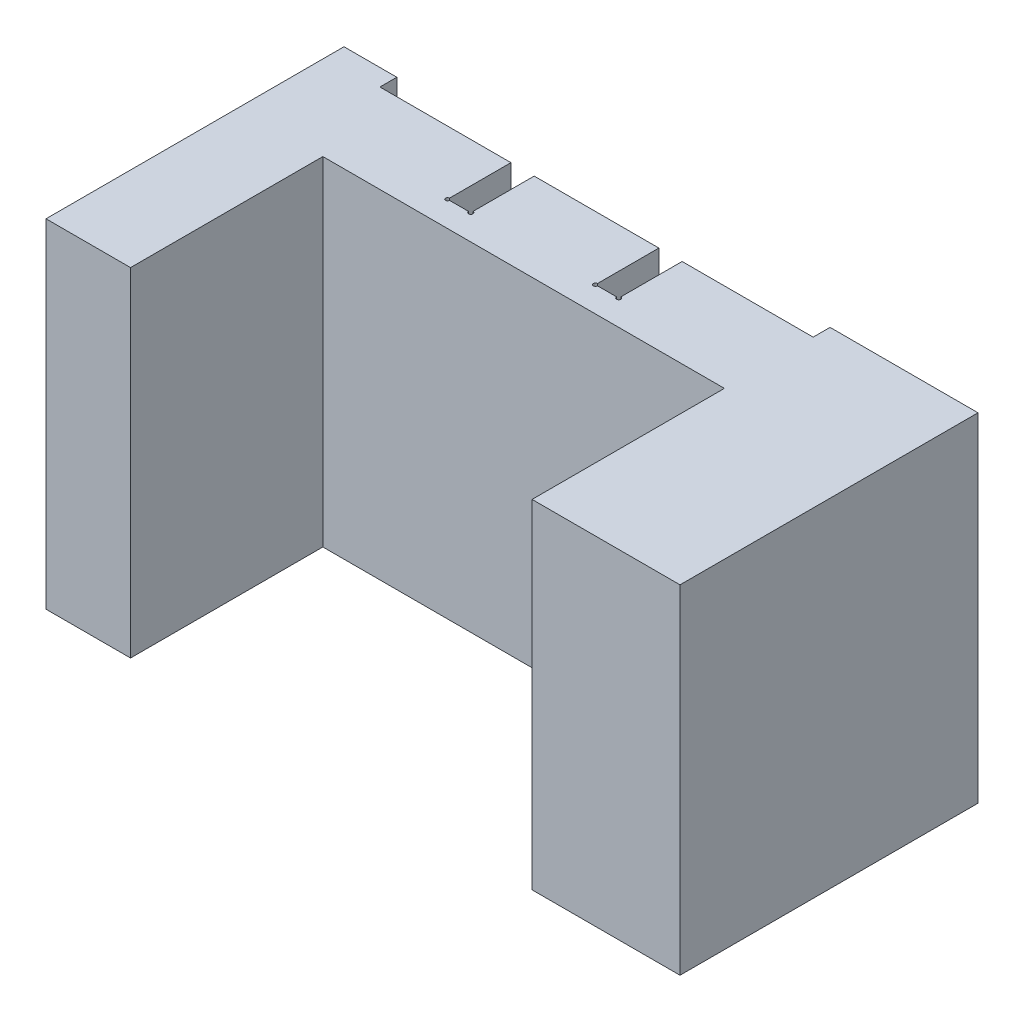
SolidWorks part; units mm, degrees
ref_plane "前视基准面" through (0, 0, 0) normal (0, 0, 1) x (1, 0, 0)
ref_plane "上视基准面" through (0, 0, 0) normal (0, 1, 0) x (1, 0, 0)
ref_plane "右视基准面" through (0, 0, 0) normal (1, 0, 0) x (0, 0, -1)
sketch "草图1" plane through (0, 0, 0) normal (0, 0, 1) x (1, 0, 0)
  line L1 (-7.5503, 16.7364) -> (22.4497, 16.7364)
  line L2 (-7.5503, 16.7364) -> (-7.5503, -11.2636)
  line L3 (-7.5503, -11.2636) -> (22.4497, -11.2636)
  line L4 (22.4497, 16.7364) -> (22.4497, -11.2636)
  dimension "D1" = 30
  dimension "D2" = 28
extrude "凸台-拉伸1" add sketch "草图1" along normal blind 10
sketch "草图2" plane through (0, 0, 0) normal (0, 0, -1) x (-1, 0, 0)
  line L0 (-22.4497, 16.7364) -> (7.5503, 16.7364) construction
  line L1 (7.5503, 16.7364) -> (7.5503, -11.2636) construction
  line L3 (5.0503, 16.7364) -> (-15.4497, 16.7364)
  line L4 (5.0503, 16.7364) -> (5.0503, 3.7364)
  line L5 (2.0503, 0.7364) -> (-12.4497, 0.7364)
  line L6 (-15.4497, 16.7364) -> (-15.4497, 3.7364)
  arc A0 (2.0503, 0.7364) -> (5.0503, 3.7364) centre (2.0503, 3.7364) ccw
  arc A1 (-12.4497, 0.7364) -> (-15.4497, 3.7364) centre (-12.4497, 3.7364) cw
  point P0 (5.0503, 16.7364)
  point P11 (5.0503, 0.7364)
  dimension "D4" = 3
  dimension "D1" = 2.5
  dimension "D2" = 20.5
  dimension "D3" = 16
extrude "切除-拉伸2" cut sketch "草图2" against normal blind 0.8
sketch "草图3" plane through (0, 0, 0.8) normal (0, 0, -1) x (-1, 0, 0)
  line L0 (5.0503, 16.7364) -> (-15.4497, 16.7364) construction
  line L2 (-15.1997, 16.7364) -> (4.8003, 16.7364)
  line L3 (-15.1997, 16.7364) -> (-15.1997, 3.7364)
  line L4 (-12.1997, 0.7364) -> (1.8003, 0.7364)
  line L5 (4.8003, 16.7364) -> (4.8003, 3.7364)
  arc A0 (1.8003, 0.7364) -> (4.8003, 3.7364) centre (1.8003, 3.7364) ccw
  arc A1 (-12.1997, 0.7364) -> (-15.1997, 3.7364) centre (-12.1997, 3.7364) cw
  point P0 (-5.1997, 16.7364)
  point P9 (4.8003, 0.7364)
  point P12 (1.8003, 13.7364)
  point P14 (-12.1997, 13.7364)
  dimension "D4" = 3
  dimension "D1" = 20
  dimension "D2" = 10
  dimension "D3" = 16
  dimension "D5" = 3
  dimension "D6" = 3
  dimension "D7" = 3
  dimension "D8" = 3
hole_wizard "M1.4x0.3 螺纹孔2" positions "草图9" profile "草图7" tap size "M1.4x0.3" standard "ANSI Metric"
sketch "草图9" plane through (0, 0, 0.8) normal (0, 0, -1) x (-1, 0, 0)
  line L0 (-15.1997, 16.7364) -> (4.8003, 16.7364) construction
  point P0 (-12.1997, 8.7364)
  point P3 (1.8003, 8.7364)
  dimension "D1" = 8
  dimension "D2" = 8
sketch "草图7" plane through (12.1997, 8.7364, 0.8) normal (1, 0, 0) x (0, 1, 0)
  line L0 (0, 0) -> (0, 4.0305)
  line L1 (0, 4.0305) -> (0.55, 3.7)
  line L2 (0.55, 3.7) -> (0.55, 0)
  line L5 (0.55, 0) -> (0, 0)
  line L10 (0, 4.0305) -> (-0.55, 3.7) construction
  line L11 (0, -6.35) -> (0, 107.95) construction
  dimension "螺纹孔钻头直径" = 1.1
  dimension "螺纹孔钻头深度" = 3.7
  dimension "导头角度" = 118
cosmetic thread "孔螺蚊线7" parameters "D1"=3.5, "D2"=1.4
cosmetic thread "孔螺蚊线8" parameters "D1"=3.5, "D2"=1.4
sketch "草图27" plane through (0, 0, 0.8) normal (0, 0, -1) x (-1, 0, 0)
  line L2 (-15.4497, 8.7364) -> (5.0503, 8.7364)
  line L3 (5.0503, 16.7364) -> (-15.4497, 16.7364) construction
  point P0 (-15.4497, 12.2364)
  point P1 (5.0503, 12.2364)
  dimension "D1" = 8
sketch "草图10" plane through (0, 16.7364, 0) normal (0, 1, 0) x (1, 0, 0)
  line L0 (22.4497, -0.8) -> (-7.5503, -0.8)
  line L1 (22.4497, -10) -> (22.4497, 0) construction
  line L2 (-7.5503, -10) -> (-7.5503, 0) construction
  line L3 (22.4497, 0) -> (15.4497, 0) construction
  line L5 (9.2497, -0.8) -> (8.1497, -0.8)
  line L6 (9.2497, -0.8) -> (9.2497, -3.7)
  line L7 (9.1495, -3.8) -> (8.2497, -3.8)
  line L8 (8.1497, -0.8) -> (8.1497, -3.7)
  line L9 (1.1497, -0.8) -> (2.2497, -0.8)
  line L10 (1.1497, -0.8) -> (1.1497, -3.7043)
  line L11 (1.2454, -3.8) -> (2.1461, -3.8)
  line L12 (2.2497, -0.8) -> (2.2497, -3.6964)
  arc A0 (9.1495, -3.8) -> (9.2497, -3.7) centre (9.2495, -3.8) ccw
  arc A1 (8.1497, -3.7) -> (8.2497, -3.8) centre (8.1497, -3.8) ccw
  arc A2 (2.1461, -3.8) -> (2.2497, -3.6964) centre (2.2497, -3.8) ccw
  arc A3 (1.1497, -3.7043) -> (1.2454, -3.8) centre (1.1497, -3.8) ccw
  point P8 (5.1997, -0.8)
  point P9 (9.2497, -0.8)
  point P10 (1.1497, -0.8)
  dimension "D9" = 0.1
  dimension "D10" = 0.1
  dimension "D1" = 0.8
  dimension "D2" = 4.05
  dimension "D3" = 4.05
  dimension "D4" = 3
  dimension "D5" = 1.1
  dimension "D6" = 1.1
  dimension "D7" = 3
  dimension "D8" = 12.75
extrude "切除-拉伸3" cut sketch "草图10" against normal blind 4 contours L8 A1 L7 A0 L6 L5 | L10 A3 L11 A2 L12 L9
sketch "草图11" plane through (0, 0, 0) normal (0, 0, -1) x (-1, 0, 0)
  line L0 (-12.1997, 0.7364) -> (1.8003, 0.7364) construction
  line L1 (-7.5497, -2.0636) -> (-2.8497, -2.0636)
  line L2 (-7.7997, 0.7364) -> (-2.5997, 0.7364)
  line L3 (-7.7997, 0.7364) -> (-7.7997, -1.8136)
  line L5 (-2.5997, 0.7364) -> (-2.5997, -1.8136)
  arc A0 (-2.8497, -2.0636) -> (-2.5997, -1.8136) centre (-2.5997, -2.0636) ccw
  arc A1 (-7.7997, -1.8136) -> (-7.5497, -2.0636) centre (-7.7997, -2.0636) ccw
  point P0 (-5.1997, 0.7364)
  dimension "D4" = 2.8
  dimension "D5" = 0.5
  dimension "D6" = 0.5
  dimension "D1" = 5.2
  dimension "D2" = 2.6
  dimension "D3" = 2.8
  dimension "D7" = 2.8
  dimension "D8" = 2.8
  dimension "D9" = 4.7
extrude "切除-拉伸4" cut sketch "草图11" against normal blind 0.5
sketch "草图12" plane through (0, 0, 0) normal (0, 0, -1) x (-1, 0, 0)
  line L0 (-22.4497, -11.2636) -> (-22.4497, 16.7364) construction
  line L1 (7.5503, -11.2636) -> (-22.4497, -11.2636)
  line L2 (7.5503, -11.2636) -> (7.5503, -7.0136)
  line L3 (7.5503, -7.0136) -> (-22.4497, -7.0136)
  line L4 (-22.4497, -11.2636) -> (-22.4497, -7.0136)
  dimension "D1" = 4.25
extrude "切除-拉伸5" cut sketch "草图12" against normal blind 10
sketch "草图14" plane through (0, 0, 10) normal (0, 0, 1) x (1, 0, 0)
  line L0 (-7.5503, -7.0136) -> (22.4497, -7.0136) construction
  line L1 (-7.5503, 16.7364) -> (15.4497, 16.7364)
  line L2 (-7.5503, 16.7364) -> (-7.5503, -7.0136)
  line L3 (-7.5503, -7.0136) -> (15.4497, -7.0136)
  line L4 (15.4497, 16.7364) -> (15.4497, -7.0136)
  line L5 (22.4497, -7.0136) -> (22.4497, 16.7364) construction
  dimension "D1" = 7
extrude "切除-拉伸7" cut sketch "草图14" against normal blind 5
sketch "草图21" plane through (0, 0, 0.8) normal (0, 0, -1) x (-1, 0, 0)
  point P0 (-5.1997, 16.7364)
sketch "草图22" plane through (0, 16.7364, 0) normal (0, 1, 0) x (1, 0, 0)
  line L0 (5.1997, -0.8) -> (5.1997, -5)
  line L1 (15.4497, -5) -> (-7.5503, -5) construction
sketch "草图23" plane through (0, 0, 5) normal (0, 0, 1) x (1, 0, 0)
  line L0 (-7.5503, -7.0136) -> (15.4497, -7.0136) construction
  line L1 (-7.5503, 16.7364) -> (-3.5503, 16.7364)
  line L2 (-7.5503, 16.7364) -> (-7.5503, -7.0136)
  line L3 (-7.5503, -7.0136) -> (-3.5503, -7.0136)
  line L4 (-3.5503, 16.7364) -> (-3.5503, -7.0136)
  dimension "D1" = 4
extrude "凸台-拉伸4" add sketch "草图23" along normal blind 9.1
sketch "草图24" plane through (0, 0, 0) normal (0, 0, -1) x (-1, 0, 0)
  line L0 (-22.4497, -7.0136) -> (-22.4497, 16.7364) construction
  line L1 (7.5503, -7.0136) -> (-22.4497, -7.0136)
  line L2 (7.5503, -7.0136) -> (7.5503, 0.7364)
  line L3 (7.5503, 0.7364) -> (-22.4497, 0.7364)
  line L4 (-22.4497, -7.0136) -> (-22.4497, 0.7364)
  dimension "D1" = 7.75
extrude "切除-拉伸8" cut sketch "草图24" against normal blind 20
sketch "草图25" plane through (0, 0, 10) normal (0, 0, 1) x (1, 0, 0)
  line L1 (22.4497, 0.7364) -> (15.4497, 0.7364)
  line L2 (22.4497, 0.7364) -> (22.4497, 16.7364)
  line L3 (22.4497, 16.7364) -> (15.4497, 16.7364)
  line L4 (15.4497, 0.7364) -> (15.4497, 16.7364)
extrude "凸台-拉伸5" add sketch "草图25" along normal blind 4.1
sketch "草图26" plane through (0, 0.7364, 0) normal (0, -1, 0) x (1, 0, 0)
  line L1 (12.4497, 0) -> (15.4497, 0)
  line L2 (12.4497, 0) -> (12.4497, 0.8)
  line L3 (12.4497, 0.8) -> (15.4497, 0.8)
  line L4 (15.4497, 0) -> (15.4497, 0.8)
  line L5 (-2.0503, 0) -> (-5.0503, 0)
  line L6 (-2.0503, 0) -> (-2.0503, 0.8)
  line L7 (-2.0503, 0.8) -> (-5.0503, 0.8)
  line L8 (-5.0503, 0) -> (-5.0503, 0.8)
  dimension "D1" = 3
  dimension "D2" = 3
  dimension "D3" = 0.8
  dimension "D4" = 0.8
extrude "切除-拉伸9" cut sketch "草图26" against normal blind 4.1
sketch "草图28" plane through (0, 0.7364, 0) normal (0, -1, 0) x (1, 0, 0)
  line L0 (12.1997, 0.8) -> (-1.8003, 0.8) construction
  line L1 (8.1497, 0.8) -> (9.2497, 0.8)
  line L2 (8.1497, 0.8) -> (8.1497, 3.8)
  line L3 (8.1497, 3.8) -> (9.2497, 3.8)
  line L4 (9.2497, 0.8) -> (9.2497, 3.8)
  line L6 (2.2497, 0.8) -> (1.1497, 0.8)
  line L7 (2.2497, 0.8) -> (2.2497, 3.8)
  line L8 (2.2497, 3.8) -> (1.1497, 3.8)
  line L9 (1.1497, 0.8) -> (1.1497, 3.8)
  point P10 (5.1997, 0.8)
  dimension "D1" = 4.05
  dimension "D2" = 2.95
  dimension "D3" = 2.95
  dimension "D4" = 4.05
  dimension "D5" = 3
  dimension "D6" = 3
sketch "草图29" plane through (0, 0.7364, 0) normal (0, -1, 0) x (1, 0, 0)
  circle A0 centre (9.2497, 3.8) radius 0.1
  circle A1 centre (8.1497, 3.8) radius 0.1
  circle A2 centre (2.2497, 3.8) radius 0.1
  circle A3 centre (1.1497, 3.8) radius 0.1
  dimension "D1" = 0.2
  dimension "D2" = 0.2
  dimension "D3" = 0.2
  dimension "D4" = 0.2
extrude "切除-拉伸11" cut sketch "草图28" against normal blind 4
extrude "切除-拉伸12" cut sketch "草图29" against normal blind 4
